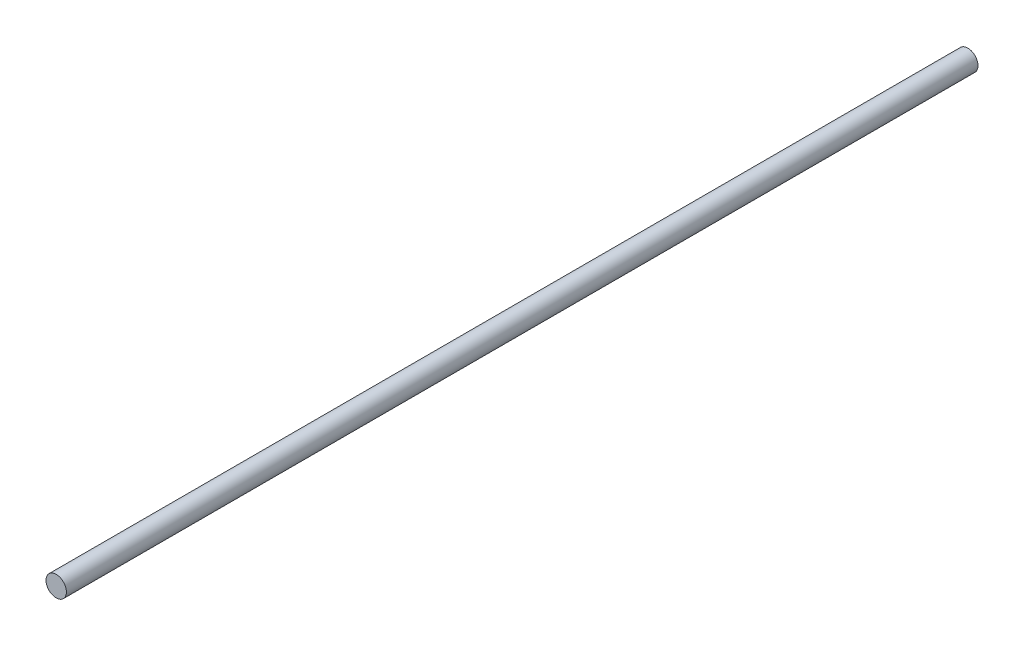
SolidWorks part; units mm, degrees
ref_plane "Front" through (0, 0, 0) normal (0, 0, 1) x (1, 0, 0)
ref_plane "Top" through (0, 0, 0) normal (0, 1, 0) x (1, 0, 0)
ref_plane "Right" through (0, 0, 0) normal (1, 0, 0) x (0, 0, -1)
sketch "草图1" plane through (0, 0, 0) normal (0, 0, 1) x (1, 0, 0)
  circle A0 centre (0, 0) radius 1.5
extrude "凸台-拉伸1" add sketch "草图1" along normal blind 134
